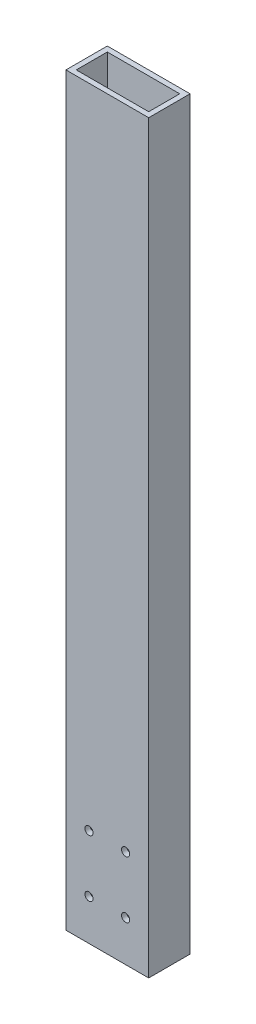
SolidWorks part; units mm, degrees
material "Thornel VCB-20 Carbon Cloth"
ref_plane "Front Plane" through (0, 0, 0) normal (0, 0, 1) x (1, 0, 0)
ref_plane "Top Plane" through (0, 0, 0) normal (0, 1, 0) x (1, 0, 0)
ref_plane "Right Plane" through (0, 0, 0) normal (1, 0, 0) x (0, 0, -1)
sketch "Sketch1" plane through (0, 0, 0) normal (0, 1, 0) x (1, 0, 0)
  line L0 (-22.225, 0) -> (-25.4, 0) construction
  line L1 (-22.225, -9.525) -> (22.225, -9.525)
  line L2 (-22.225, -9.525) -> (-22.225, 9.525)
  line L3 (-22.225, 9.525) -> (22.225, 9.525)
  line L4 (22.225, -9.525) -> (22.225, 9.525)
  line L5 (-22.225, -9.525) -> (22.225, 9.525) construction
  line L6 (-22.225, 9.525) -> (22.225, -9.525) construction
  line L7 (-25.4, -12.7) -> (25.4, -12.7)
  line L8 (-25.4, -12.7) -> (-25.4, 12.7)
  line L9 (-25.4, 12.7) -> (25.4, 12.7)
  line L10 (25.4, -12.7) -> (25.4, 12.7)
  line L11 (-25.4, -12.7) -> (25.4, 12.7) construction
  line L12 (-25.4, 12.7) -> (25.4, -12.7) construction
  line L13 (0, -9.525) -> (0, -12.7) construction
  point P0 (0, 0)
  point P6 (0, 0)
  dimension "D1" = 50.8
  dimension "D2" = 25.4
  dimension "D3" = 3.175
extrude "Boss-Extrude1" add sketch "Sketch1" along normal blind 457.2
sketch "Sketch2" plane through (0, 0, 12.7) normal (0, 0, 1) x (1, 0, 0)
  line L1 (-11.25, 25) -> (11.25, 25) construction
  line L2 (-11.25, 25) -> (-11.25, 60) construction
  line L3 (-11.25, 60) -> (11.25, 60) construction
  line L4 (11.25, 25) -> (11.25, 60) construction
  circle A0 centre (-11.25, 60) radius 2.5
  circle A1 centre (-11.25, 25) radius 2.5
  circle A2 centre (11.25, 25) radius 2.5
  circle A3 centre (11.25, 60) radius 2.5
  point P4 (0, 25)
  dimension "D4" = 5
  dimension "D1" = 22.5
  dimension "D2" = 35
  dimension "D3" = 25
extrude "Cut-Extrude1" cut sketch "Sketch2" against normal through all
equation "\"tube_width\"= 1in"
equation "\"tube_height\"= 2in"
equation "\"tube_thickness\"= 0.125in"
equation "\"D2@Sketch1\"=\"tube_width\""
equation "\"D1@Sketch1\"=\"tube_height\""
equation "\"D3@Sketch1\"=\"tube_thickness\""
equation "\"tube_length\"= 1.5ft"
equation "\"D1@Boss-Extrude1\"=\"tube_length\""
